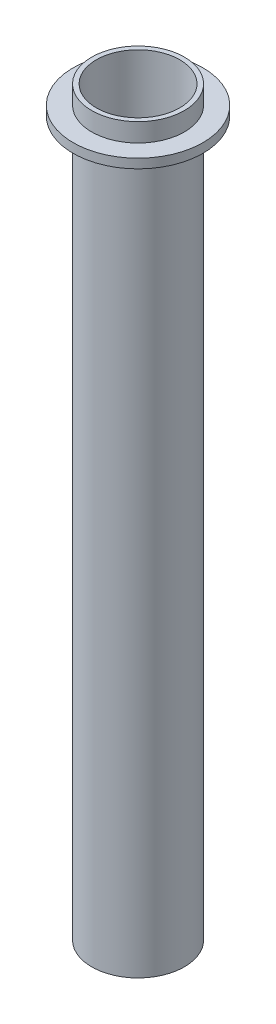
SolidWorks part; units mm, degrees
ref_plane "Front Plane" through (0, 0, 0) normal (0, 0, 1) x (1, 0, 0)
ref_plane "Top Plane" through (0, 0, 0) normal (0, 1, 0) x (1, 0, 0)
ref_plane "Right Plane" through (0, 0, 0) normal (1, 0, 0) x (0, 0, -1)
sketch "Sketch2" plane through (0, 0, 0) normal (0, 0, 1) x (1, 0, 0)
  line L0 (-7.1437, 0) -> (-7.1437, 127)
  line L1 (-7.1437, 0) -> (-7.9375, 0)
  line L2 (0, 0) -> (0, 127) construction
  line L3 (-7.1437, 127) -> (-7.9375, 127)
  line L4 (-7.9375, 0) -> (-7.9375, 122.2375)
  line L5 (-7.1437, 127) -> (0, 127) construction
  line L6 (-7.1437, 0) -> (0, 0) construction
  line L7 (-7.9375, 123.825) -> (-11.1125, 123.825)
  line L8 (-11.1125, 123.825) -> (-11.1125, 122.2375)
  line L9 (-11.1125, 122.2375) -> (-7.9375, 122.2375)
  line L10 (-7.9375, 123.825) -> (-7.9375, 127)
  dimension "D1" = 7.9375
  dimension "D2" = 0.7937
  dimension "D3" = 127
  dimension "D4" = 3.175
  dimension "D5" = 1.5875
  dimension "D6" = 3.175
revolve "Revolve1" add sketch "Sketch2" angle 360 about L2
